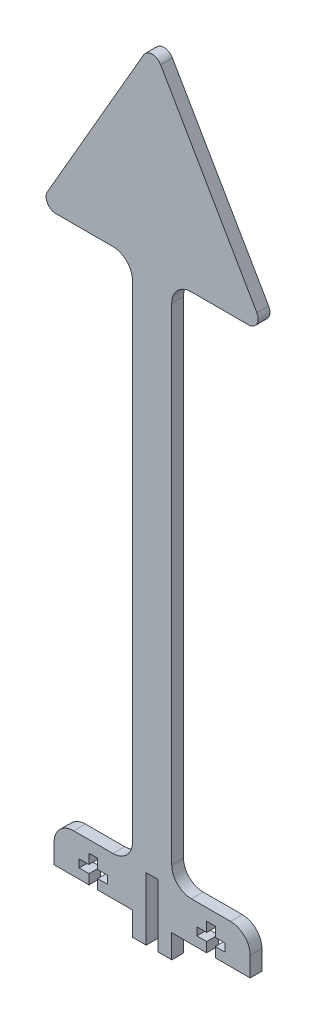
SolidWorks part; units mm, degrees
ref_plane "Front Plane" through (0, 0, 0) normal (0, 0, 1) x (1, 0, 0)
ref_plane "Top Plane" through (0, 0, 0) normal (0, 1, 0) x (1, 0, 0)
ref_plane "Right Plane" through (0, 0, 0) normal (1, 0, 0) x (0, 0, -1)
sketch "Sketch1" plane through (0, 0, 0) normal (0, 0, 1) x (1, 0, 0)
  line L0 (-5, -25) -> (-5, -159)
  line L1 (-28.8675, -25) -> (-5, -25)
  line L5 (-28.8675, -25) -> (0, 25)
  line L6 (0, 25) -> (28.8675, -25)
  line L7 (-5, -175) -> (-1.5, -175)
  line L8 (5, -175) -> (5, -169)
  line L9 (5, -25) -> (28.8675, -25)
  line L10 (-5, -169) -> (-13.9, -169)
  line L11 (-25, -169) -> (-25, -159)
  line L12 (-25, -159) -> (-5, -159)
  line L13 (-16.1, -169) -> (-16.1, -166.5)
  line L14 (0, 25) -> (0, -175) construction
  line L15 (-16.1, -166.5) -> (-18.6, -166.5)
  line L16 (-18.6, -166.5) -> (-18.6, -164.5)
  line L17 (-18.6, -164.5) -> (-16.1, -164.5)
  line L18 (-16.1, -164.5) -> (-16.1, -162)
  line L19 (-16.1, -162) -> (-13.9, -162)
  line L20 (-13.9, -162) -> (-13.9, -164.5)
  line L21 (-13.9, -164.5) -> (-11.4, -164.5)
  line L22 (-11.4, -164.5) -> (-11.4, -166.5)
  line L23 (-11.4, -166.5) -> (-13.9, -166.5)
  line L24 (-13.9, -166.5) -> (-13.9, -169)
  line L25 (-15, -159) -> (-15, -169) construction
  line L26 (15, -159) -> (15, -169) construction
  line L27 (13.9, -166.5) -> (13.9, -169)
  line L28 (11.4, -166.5) -> (13.9, -166.5)
  line L29 (11.4, -164.5) -> (11.4, -166.5)
  line L30 (13.9, -164.5) -> (11.4, -164.5)
  line L31 (13.9, -162) -> (13.9, -164.5)
  line L32 (16.1, -162) -> (13.9, -162)
  line L33 (16.1, -164.5) -> (16.1, -162)
  line L34 (18.6, -164.5) -> (16.1, -164.5)
  line L35 (18.6, -166.5) -> (18.6, -164.5)
  line L36 (16.1, -166.5) -> (18.6, -166.5)
  line L37 (16.1, -169) -> (16.1, -166.5)
  line L38 (25, -159) -> (5, -159)
  line L39 (25, -169) -> (25, -159)
  line L40 (5, -169) -> (13.9, -169)
  line L41 (-16.1, -169) -> (-25, -169)
  line L42 (16.1, -169) -> (25, -169)
  line L43 (5, -159) -> (5, -25)
  line L44 (-5, -169) -> (-5, -175)
  line L45 (-1.5, -175) -> (-1.5, -159)
  line L46 (-1.5, -159) -> (1.5, -159)
  line L47 (1.5, -159) -> (1.5, -175)
  line L48 (1.5, -175) -> (5, -175)
  point P0 (0, 0)
  point P36 (-15, -162)
  point P57 (0, -159)
  dimension "D3" = 200
  dimension "D2" = 25
  dimension "D4" = 25
  dimension "D5" = 5
  dimension "D6" = 23.8675
  dimension "D7" = 23.8675
  dimension "D8" = 150
  dimension "D9" = 10
  dimension "D10" = 20
  dimension "D11" = 6
  dimension "D12" = 2.5
  dimension "D13" = 2
  dimension "D14" = 2.5
  dimension "D15" = 2.5
  dimension "D16" = 2.2
  dimension "D17" = 2.5
  dimension "D18" = 16
  dimension "D19" = 1.5
  dimension "D20" = 28.8675
extrude "Boss-Extrude1" add sketch "Sketch1" along normal blind 3
fillet "Fillet1" radius 5 6 edges at (-5, -159, 1.5) (5, -159, 1.5) (-5, -25, 1.5) (5, -25, 1.5) (25, -159, 1.5) (-25, -159, 1.5)
fillet "Fillet2" radius 2.5 3 edges at (28.8675, -25, 1.5) (0, 25, 1.5) (-28.8675, -25, 1.5)
